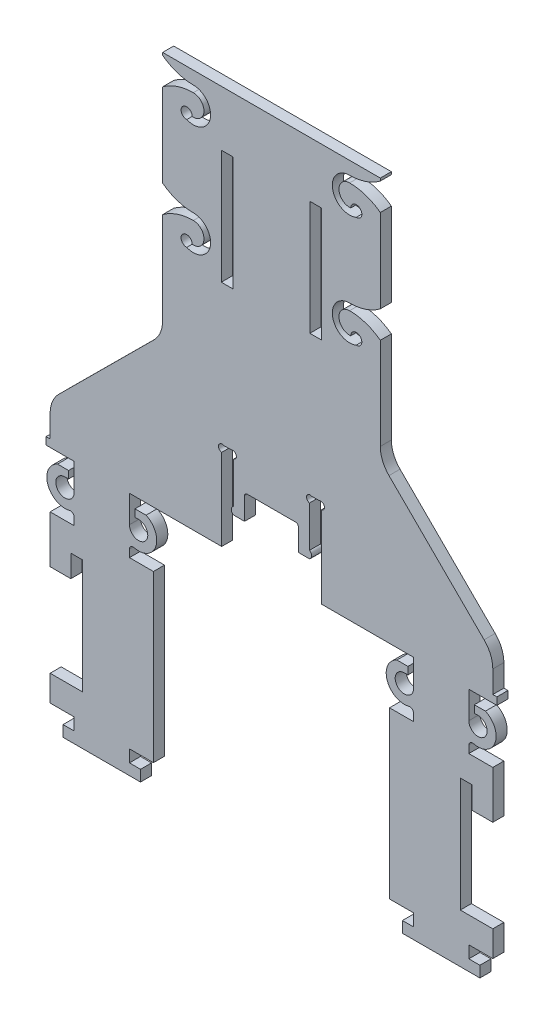
SolidWorks part; units mm, degrees
ref_plane "Front Plane" through (0, 0, 0) normal (0, 0, 1) x (1, 0, 0)
ref_plane "Top Plane" through (0, 0, 0) normal (0, 1, 0) x (1, 0, 0)
ref_plane "Right Plane" through (0, 0, 0) normal (1, 0, 0) x (0, 0, -1)
sketch "Sketch1" plane through (0, 0, 0) normal (0, 0, 1) x (1, 0, 0)
  line L0 (0, 63) -> (0, 158.4589) construction
  line L1 (0, 91.6123) -> (0, 244.3753) construction
  line L2 (-29.5, 171) -> (29.5, 171)
  line L3 (29.5, 171) -> (29.5, 108)
  line L4 (31.8572, 102.3292) -> (57.6428, 76.6708)
  line L5 (60, 71) -> (60, 63)
  line L10 (-60, 71) -> (-60, 63)
  line L11 (-31.8572, 102.3292) -> (-57.6428, 76.6708)
  line L12 (-29.5, 171) -> (-29.5, 108)
  line L25 (60, 63) -> (0, 63)
  line L37 (-60, 63) -> (0, 63)
  arc A0 (29.5, 108) -> (31.8572, 102.3292) centre (37.5, 108) ccw
  arc A1 (57.6428, 76.6708) -> (60, 71) centre (52, 71) cw
  arc A2 (-57.6428, 76.6708) -> (-60, 71) centre (-52, 71) ccw
  arc A3 (-29.5, 108) -> (-31.8572, 102.3292) centre (-37.5, 108) cw
  point P32 (0, 171)
  dimension "D2" = 8
  dimension "D1" = 8
  dimension "D3" = 45
  dimension "D4" = 59
  dimension "D5" = 60
extrude "main spar" add sketch "Sketch1" along normal up to vertex (3 mm away)
sketch "Sketch10" plane through (0, 0, 0) normal (0, 0, -1) x (-1, 0, 0)
  line B0 (53.5, 63) -> (53.5, 55.6162)
  line B1 (53.5, 49.8891) -> (53.5, 47.8891)
  line B2 (58, 60.1) -> (55, 60.1)
  line B3 (55.9838, 58.1) -> (55, 58.1)
  line B4 (38.5, 49.8891) -> (38.5, 47.8891)
  line B5 (34, 60.1) -> (37, 60.1)
  line B6 (37, 60.1) -> (37, 58.1)
  line B7 (38.5, 63) -> (38.5, 55.6162)
  line B8 (55, 58.1) -> (55, 60.1)
  line B9 (37, 58.1) -> (36.0162, 58.1)
  arc B10 (53.5, 55.6162) -> (55.9838, 58.1) centre (55.9838, 55.6162) ccw
  arc B11 (37.2492, 50.8571) -> (38.5, 49.8891) centre (37.5, 49.8891) cw
  arc B12 (58, 60.1) -> (54.7508, 50.8571) centre (55.9838, 55.6162) cw
  arc B13 (54.7508, 50.8571) -> (53.5, 49.8891) centre (54.5, 49.8891) ccw
  arc B14 (34, 60.1) -> (37.2492, 50.8571) centre (36.0162, 55.6162) ccw
  arc B15 (38.5, 55.6162) -> (36.0162, 58.1) centre (36.0162, 55.6162) cw
  line B16 (53.5, 47.8891) -> (38.5, 47.8891)
  line B17 (53.5, 63) -> (61.1, 63)
  line B18 (38.5, 63) -> (30.9, 63)
  line B19 (61.1, 63) -> (61.1, 65)
  line B20 (61.1, 65) -> (30.9, 65)
  line B21 (30.9, 65) -> (30.9, 63)
  line B22 (-38.5, 63) -> (-38.5, 55.6162)
  line B23 (-38.5, 49.8891) -> (-38.5, 47.8891)
  line B24 (-34, 60.1) -> (-37, 60.1)
  line B25 (-36.0162, 58.1) -> (-37, 58.1)
  line B26 (-53.5, 49.8891) -> (-53.5, 47.8891)
  line B27 (-58, 60.1) -> (-55, 60.1)
  line B28 (-55, 60.1) -> (-55, 58.1)
  line B29 (-53.5, 63) -> (-53.5, 55.6162)
  line B30 (-37, 58.1) -> (-37, 60.1)
  line B31 (-55, 58.1) -> (-55.9838, 58.1)
  arc B32 (-38.5, 55.6162) -> (-36.0162, 58.1) centre (-36.0162, 55.6162) ccw
  arc B33 (-54.7508, 50.8571) -> (-53.5, 49.8891) centre (-54.5, 49.8891) cw
  arc B34 (-34, 60.1) -> (-37.2492, 50.8571) centre (-36.0162, 55.6162) cw
  arc B35 (-37.2492, 50.8571) -> (-38.5, 49.8891) centre (-37.5, 49.8891) ccw
  arc B36 (-58, 60.1) -> (-54.7508, 50.8571) centre (-55.9838, 55.6162) ccw
  arc B37 (-53.5, 55.6162) -> (-55.9838, 58.1) centre (-55.9838, 55.6162) cw
  line B38 (-38.5, 47.8891) -> (-53.5, 47.8891)
  line B39 (-38.5, 63) -> (-30.9, 63)
  line B40 (-53.5, 63) -> (-61.1, 63)
  line B41 (-30.9, 63) -> (-30.9, 65)
  line B42 (-30.9, 65) -> (-61.1, 65)
  line B43 (-61.1, 65) -> (-61.1, 63)
sketch_block_instance "T-slot-tab-1"
sketch_block "T-slot-tab" parameters "D2"=1, "D18"=1, "D1"=5, "D3"=0.5, "D4"=15, "D5"=0.2, "D6"=3.1, "D7"=1.5, "D8"=30, "D9"=3.5, "D10"=5, "D11"=10, "D12"=2.5, "D13"=5, "D14"=6, "D15"=7.3, "D16"=0.2, "D17"=1.5, "D19"=15, "D20"=2, "D21"=2.9
sketch_block_instance "T-slot-tab-2"
extrude "T tabs top plate" add sketch "Sketch10" against normal up to surface (3 mm away) up to face at (0, 98.6667, 3)
sketch "Sketch11" plane through (0, 0, 0) normal (0, 0, -1) x (-1, 0, 0)
  line L0 (38.5, 47.8891) -> (53.5, 47.8891) construction
  line L1 (32, 47.8891) -> (60, 47.8891)
  line L2 (32, 47.8891) -> (32, 3)
  line L3 (32, 3) -> (38.5, 3)
  line L4 (60, 47.8891) -> (60, 3)
  line L5 (-53.5, 47.8891) -> (-38.5, 47.8891) construction
  line L6 (-60, 47.8891) -> (-32, 47.8891)
  line L7 (-60, 47.8891) -> (-60, 3)
  line L8 (0, 0) -> (0, 16.634) construction
  line L9 (-32, 47.8891) -> (-32, 3)
  line L10 (53.5, 3) -> (53.5, -0.3)
  line L11 (53.5, -0.3) -> (56.5, -0.3)
  line L12 (56.5, -0.3) -> (56.5, -3.3)
  line L13 (56.5, -3.3) -> (35.5, -3.3)
  line L14 (35.5, -3.3) -> (35.5, -0.3)
  line L15 (35.5, -0.3) -> (38.5, -0.3)
  line L16 (38.5, -0.3) -> (38.5, 3)
  line L17 (53.5, 3) -> (60, 3)
  line L18 (73.2817, 3) -> (0, 3) construction
  line L19 (0, 0) -> (73.2817, 0) construction
  line L20 (46, 0) -> (46, -7.0628) construction
  line L21 (-32, 3) -> (-38.5, 3)
  line L22 (-38.5, -0.3) -> (-38.5, 3)
  line L23 (-35.5, -0.3) -> (-38.5, -0.3)
  line L24 (-35.5, -3.3) -> (-35.5, -0.3)
  line L25 (-56.5, -3.3) -> (-35.5, -3.3)
  line L26 (-56.5, -0.3) -> (-56.5, -3.3)
  line L27 (-53.5, -0.3) -> (-56.5, -0.3)
  line L28 (-53.5, 3) -> (-53.5, -0.3)
  line L29 (-53.5, 3) -> (-60, 3)
  line L31 (53.5, 0) -> (53.5, 3) construction
  line L32 (53.5, 0) -> (53.5, 3) construction
  dimension "D1" = 3
  dimension "D2" = 0.3
  dimension "D4" = 3
extrude "long tab" add sketch "Sketch11" against normal up to surface (3 mm away) up to face at (0, 66.1898, 3)
sketch "Sketch2" plane through (0, 0, 3) normal (0, 0, 1) x (1, 0, 0)
  line L0 (0, 53.1) -> (0, 168.6269) construction
  line L1 (29.5, 171) -> (-29.5, 171) construction
  line L2 (13.5, 153.0365) -> (13.5, 0) construction
  line L4 (10.5, 0) -> (10.5, 153.0579) construction
  line L5 (10.4, 156) -> (13.6, 156)
  line L6 (10.4, 156) -> (10.4, 125)
  line L7 (10.4, 125) -> (13.6, 125)
  line L8 (13.6, 156) -> (13.6, 125)
  line L9 (-38.5, 63) -> (38.5, 63) construction
  line L23 (-13.6, 156) -> (-13.6, 125)
  line L24 (-10.4, 125) -> (-13.6, 125)
  line L25 (-10.4, 156) -> (-10.4, 125)
  line L26 (-10.4, 156) -> (-13.6, 156)
  line L31 (0, 60) -> (0, 249.4547) construction
  line B0 (10.3, 72) -> (7.3, 72)
  line B1 (10.3, 74) -> (10.3, 85.1202)
  line B2 (7.3, 72) -> (7.3, 78)
  line B3 (13.5, 72) -> (13.5, 85.1083)
  line B4 (10.9359, 87) -> (12.9359, 87)
  arc B5 (7.3, 78) -> (5.8, 78) centre (6.55, 78) ccw
  arc B6 (10.3, 72) -> (10.3, 74) centre (9.7667, 73) ccw
  arc B7 (10.3, 85.1202) -> (10.9359, 87) centre (10.5, 86.1) cw
  arc B8 (13.5, 85.1083) -> (12.9359, 87) centre (13.3718, 86.1) ccw
  line B9 (5.8, 78) -> (5.8, 57)
  line B10 (5.8, 57) -> (13.5, 57)
  line B11 (13.5, 57) -> (13.5, 72)
  line B12 (-10.3, 72) -> (-7.3, 72)
  line B13 (-10.3, 74) -> (-10.3, 85.1202)
  line B14 (-7.3, 72) -> (-7.3, 78)
  line B15 (-13.5, 72) -> (-13.5, 85.1083)
  line B16 (-10.9359, 87) -> (-12.9359, 87)
  arc B17 (-7.3, 78) -> (-5.8, 78) centre (-6.55, 78) cw
  arc B18 (-10.3, 72) -> (-10.3, 74) centre (-9.7667, 73) cw
  arc B19 (-10.3, 85.1202) -> (-10.9359, 87) centre (-10.5, 86.1) ccw
  arc B20 (-13.5, 85.1083) -> (-12.9359, 87) centre (-13.3718, 86.1) cw
  line B21 (-5.8, 78) -> (-5.8, 57)
  line B22 (-5.8, 57) -> (-13.5, 57)
  line B23 (-13.5, 57) -> (-13.5, 72)
  dimension "D1" = 31
  dimension "D2" = 15
  dimension "D3" = 24
  dimension "D4" = 0.1
  dimension "D5" = 0.1
sketch_block_instance "plate-interleave-1"
sketch_block "plate-interleave" parameters "D2"=0.75, "D6"=1, "D1"=3.2, "D3"=6, "D4"=2, "D5"=3, "D7"=0.2, "D8"=2, "D9"=2.9, "D10"=3, "D11"=18.7475, "D12"=3, "D13"=20
sketch_block_instance "plate-interleave-3"
extrude "tab slots" cut sketch "Sketch2" against normal through all
sketch "Sketch9" plane through (0, 0, 3) normal (0, 0, 1) x (1, 0, 0)
  line L0 (-6.55, 78.75) -> (6.55, 78.75)
  line L1 (6.55, 78.75) -> (6.55, 63)
  line L2 (6.55, 63) -> (-6.55, 63)
  line L3 (-6.55, 63) -> (-6.55, 78.75)
  line L4 (-5.8, 63) -> (5.8, 63) construction
  arc A0 (-5.8, 78) -> (-7.3, 78) centre (-6.55, 78) ccw construction
  arc A1 (7.3, 78) -> (5.8, 78) centre (6.55, 78) ccw construction
extrude "tab slot extra relief and cable clearance" cut sketch "Sketch9" against normal up to next
sketch "Sketch3" plane through (0, 0, 3) normal (0, 0, 1) x (1, 0, 0)
  line L0 (29.5, 171) -> (-29.5, 171) construction
  line L4 (0, 0) -> (0, 202.9036) construction
  line B0 (-4.55, 97.4019) -> (-4.55, 101.5)
  line B1 (4.55, 97.4019) -> (4.55, 101.5)
  arc B2 (-2.3, 98.701) -> (-4.55, 97.4019) centre (-3.05, 97.4019) cw
  arc B3 (2.3, 98.701) -> (4.55, 97.4019) centre (3.05, 97.4019) ccw
  line B4 (1.55, 101.5) -> (-1.55, 101.5)
  line B5 (-1.55, 104.5) -> (1.55, 104.5)
  arc B6 (2.3, 98.701) -> (1.55, 101.5) centre (1.55, 100) ccw
  arc B7 (-4.55, 101.5) -> (-1.55, 104.5) centre (-1.55, 101.5) cw
  arc B8 (-2.3, 98.701) -> (-1.55, 101.5) centre (-1.55, 100) cw
  arc B9 (4.55, 101.5) -> (1.55, 104.5) centre (1.55, 101.5) ccw
  line B10 (-4.55, 129.4019) -> (-4.55, 133.5)
  line B11 (4.55, 129.4019) -> (4.55, 133.5)
  arc B12 (-2.3, 130.701) -> (-4.55, 129.4019) centre (-3.05, 129.4019) cw
  arc B13 (2.3, 130.701) -> (4.55, 129.4019) centre (3.05, 129.4019) ccw
  line B14 (1.55, 133.5) -> (-1.55, 133.5)
  line B15 (-1.55, 136.5) -> (1.55, 136.5)
  arc B16 (2.3, 130.701) -> (1.55, 133.5) centre (1.55, 132) ccw
  arc B17 (-4.55, 133.5) -> (-1.55, 136.5) centre (-1.55, 133.5) cw
  arc B18 (-2.3, 130.701) -> (-1.55, 133.5) centre (-1.55, 132) cw
  arc B19 (4.55, 133.5) -> (1.55, 136.5) centre (1.55, 133.5) ccw
  dimension "D1" = 66.5
  dimension "D2" = 32
sketch_block_instance "hook-1"
sketch_block "hook" parameters "D1"=2.5, "D2"=1.5, "D5"=6, "D3"=3, "D4"=3.1
sketch_block_instance "hook-2"
extrude "elastic anchor" [suppressed] cut sketch "Sketch3" against normal through all
sketch "Sketch4" plane through (0, 0, 3) normal (0, 0, 1) x (1, 0, 0)
  line L0 (-60, 35) -> (-54.39, 35)
  line L2 (-54.39, 35) -> (-54.39, 41)
  line L3 (-54.39, 41) -> (-51.19, 41)
  line L4 (-51.19, 41) -> (-51.19, 10)
  line L5 (-51.19, 10) -> (-60, 10)
  line L6 (-60, 35) -> (-60, 10)
  line L7 (-63.7311, 0) -> (0, 0) construction
  line L9 (-60, 47.8891) -> (-60, 3) construction
  line L10 (-54.19, 41) -> (-54.19, 24.5168) construction
  dimension "D1" = 0.2
  dimension "D2" = 25
  dimension "D3" = 6
  dimension "D4" = 10
extrude "side plate slot" cut sketch "Sketch4" against normal through all
mirror "side plate slot mirror" about plane through (0, 0, 0) normal (1, 0, 0) of "side plate slot"
sketch "Sketch8" plane through (0, 0, 3) normal (0, 0, 1) x (1, 0, 0)
  line L0 (46.21, 160) -> (-46.6884, 160) construction
  line L1 (0, 0) -> (0, 216.6626) construction
  line L2 (46.21, 130) -> (-46.6884, 130) construction
  line L3 (13.5, 168.9587) -> (13.5, 0) construction
  arc B0 (22.9641, 158.5004) -> (21.5004, 159.9641) centre (23, 160) ccw
  arc B1 (21.5004, 159.9641) -> (21.178, 165.7021) centre (21.178, 162.8241) cw
  arc B2 (22.9641, 158.5004) -> (21.178, 167.5021) centre (21.178, 162.8241) cw
  arc B3 (21.178, 165.7021) -> (28.5, 163.6021) centre (21.178, 151.8875) cw
  arc B4 (21.178, 167.5021) -> (28.5, 169.6021) centre (21.178, 181.3167) ccw
  line B5 (34.5, 177.6604) -> (34.5, 155.5437)
  arc B6 (28.5, 163.6021) -> (34.5, 155.5437) centre (21.178, 151.8875) cw
  line B7 (28.5, 160) -> (23, 160) construction
  line B8 (34.5, 166.6021) -> (28.5, 166.6021) construction
  line B9 (28.5, 169.6021) -> (28.5, 163.6021) construction
  line B10 (23, 160) -> (18.7574, 155.7574) construction
  arc B11 (28.5, 169.6021) -> (34.5, 177.6604) centre (21.178, 181.3167) ccw
  arc B12 (22.9641, 128.5004) -> (21.5004, 129.9641) centre (23, 130) ccw
  arc B13 (21.5004, 129.9641) -> (21.178, 135.7021) centre (21.178, 132.8241) cw
  arc B14 (22.9641, 128.5004) -> (21.178, 137.5021) centre (21.178, 132.8241) cw
  arc B15 (21.178, 135.7021) -> (28.5, 133.6021) centre (21.178, 121.8875) cw
  arc B16 (21.178, 137.5021) -> (28.5, 139.6021) centre (21.178, 151.3167) ccw
  line B17 (34.5, 147.6604) -> (34.5, 125.5437)
  arc B18 (28.5, 133.6021) -> (34.5, 125.5437) centre (21.178, 121.8875) cw
  line B19 (28.5, 130) -> (23, 130) construction
  line B20 (34.5, 136.6021) -> (28.5, 136.6021) construction
  line B21 (28.5, 139.6021) -> (28.5, 133.6021) construction
  line B22 (23, 130) -> (18.7574, 125.7574) construction
  arc B23 (28.5, 139.6021) -> (34.5, 147.6604) centre (21.178, 151.3167) ccw
  arc B24 (-22.9641, 128.5004) -> (-21.5004, 129.9641) centre (-23, 130) cw
  arc B25 (-21.5004, 129.9641) -> (-21.178, 135.7021) centre (-21.178, 132.8241) ccw
  arc B26 (-22.9641, 128.5004) -> (-21.178, 137.5021) centre (-21.178, 132.8241) ccw
  arc B27 (-21.178, 135.7021) -> (-28.5, 133.6021) centre (-21.178, 121.8875) ccw
  arc B28 (-21.178, 137.5021) -> (-28.5, 139.6021) centre (-21.178, 151.3167) cw
  line B29 (-34.5, 147.6604) -> (-34.5, 125.5437)
  arc B30 (-28.5, 133.6021) -> (-34.5, 125.5437) centre (-21.178, 121.8875) ccw
  arc B31 (-28.5, 139.6021) -> (-34.5, 147.6604) centre (-21.178, 151.3167) cw
  arc B32 (-22.9641, 158.5004) -> (-21.5004, 159.9641) centre (-23, 160) cw
  arc B33 (-21.5004, 159.9641) -> (-21.178, 165.7021) centre (-21.178, 162.8241) ccw
  arc B34 (-22.9641, 158.5004) -> (-21.178, 167.5021) centre (-21.178, 162.8241) ccw
  arc B35 (-21.178, 165.7021) -> (-28.5, 163.6021) centre (-21.178, 151.8875) ccw
  arc B36 (-21.178, 167.5021) -> (-28.5, 169.6021) centre (-21.178, 181.3167) cw
  line B37 (-34.5, 177.6604) -> (-34.5, 155.5437)
  arc B38 (-28.5, 163.6021) -> (-34.5, 155.5437) centre (-21.178, 151.8875) ccw
  arc B39 (-28.5, 169.6021) -> (-34.5, 177.6604) centre (-21.178, 181.3167) cw
  dimension "D1" = 3
sketch_block_instance "elastic-anchor-edge-slot-4"
sketch_block "elastic-anchor-edge-slot" parameters "D1"=3, "D4"=2.397, "D2"=1.5, "D3"=6, "D5"=6, "D6"=11.5, "D7"=6
sketch_block_instance "elastic-anchor-edge-slot-5"
sketch_block_instance "elastic-anchor-edge-slot-7"
sketch_block_instance "elastic-anchor-edge-slot-8"
extrude "elastic anchors" cut sketch "Sketch8" against normal up to next
